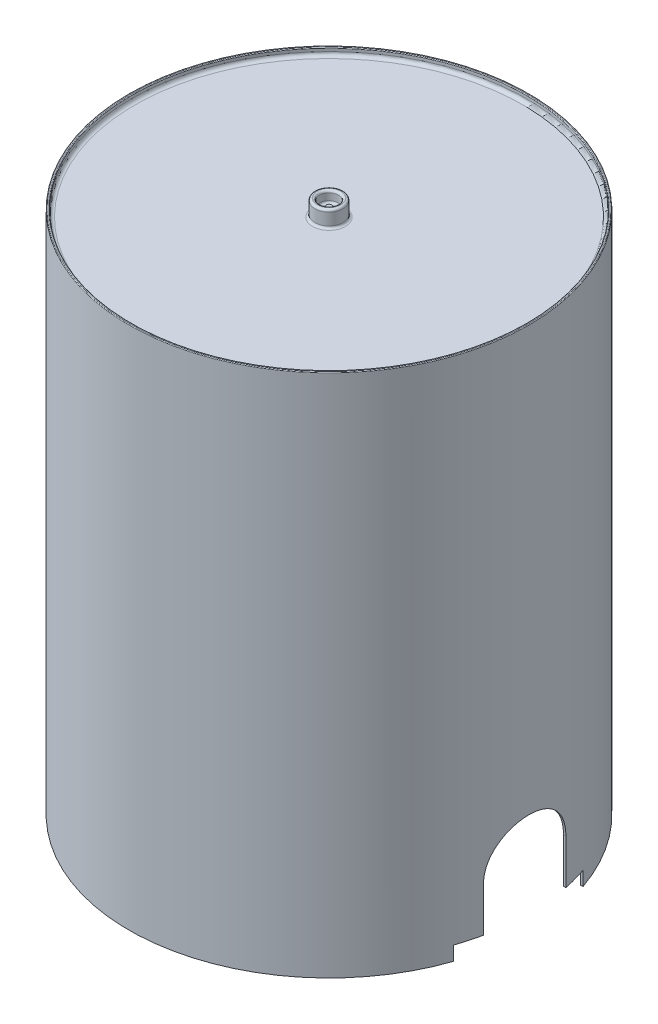
SolidWorks part; units mm, degrees
ref_plane "Plan de face" through (0, 0, 0) normal (0, 0, 1) x (1, 0, 0)
ref_plane "Plan de dessus" through (0, 0, 0) normal (0, 1, 0) x (1, 0, 0)
ref_plane "Plan de droite" through (0, 0, 0) normal (1, 0, 0) x (0, 0, -1)
sketch "Esquisse2" plane through (0, 0, 0) normal (0, 0, 1) x (1, 0, 0)
  line L0 (0, 220) -> (0, 219)
  line L1 (0, 0) -> (85, 0) construction
  line L2 (0, 0) -> (0, 220) construction
  line L3 (0, 220) -> (85, 220) construction
  line L4 (85, 0) -> (85, 220)
  line L5 (0, 219) -> (79, 219)
  line L6 (84, 214) -> (84, 0)
  line L7 (84, 0) -> (85, 0)
  line L8 (0, 220) -> (0, 224)
  line L9 (0, 224) -> (1, 224)
  line L10 (1, 224) -> (1, 223.1941)
  line L11 (1.95, 222.2441) -> (3.05, 222.2441)
  line L12 (4, 223.1941) -> (4, 226.05)
  line L13 (4.95, 227) -> (5.05, 227)
  line L14 (6, 226.05) -> (6, 220.95)
  line L15 (85, 220) -> (85, 222.7)
  line L16 (84.7, 223) -> (84.3, 223)
  line L17 (84, 222.7) -> (84, 221.5)
  line L18 (82.5, 220) -> (6.95, 220)
  arc A0 (84, 221.5) -> (82.5, 220) centre (82.5, 221.5) cw
  arc A1 (85, 222.7) -> (84.7, 223) centre (84.7, 222.7) ccw
  arc A2 (5.05, 227) -> (6, 226.05) centre (5.05, 226.05) cw
  arc A3 (4, 226.05) -> (4.95, 227) centre (4.95, 226.05) cw
  arc A4 (6, 220.95) -> (6.95, 220) centre (6.95, 220.95) ccw
  arc A5 (3.05, 222.2441) -> (4, 223.1941) centre (3.05, 223.1941) ccw
  arc A6 (1, 223.1941) -> (1.95, 222.2441) centre (1.95, 223.1941) ccw
  arc A7 (84.3, 223) -> (84, 222.7) centre (84.3, 222.7) ccw
  arc A8 (84, 214) -> (79, 219) centre (79, 214) ccw
  point P22 (6, 227)
  point P25 (4, 227)
  point P28 (6, 220)
  point P31 (4, 222.2441)
  point P34 (1, 222.2441)
  point P35 (84, 220)
  point P38 (85, 223)
  point P41 (84, 223)
  dimension "D5" = 1
  dimension "D11" = 0.95
  dimension "D13" = 1.5
  dimension "D14" = 0.3
  dimension "D15" = 5
  dimension "D1" = 85
  dimension "D2" = 220
  dimension "D3" = 1
  dimension "D4" = 1
  dimension "D6" = 4
  dimension "D7" = 7
  dimension "D8" = 1
  dimension "D9" = 3
  dimension "D10" = 2
  dimension "D12" = 3
revolve "Révolution1" add sketch "Esquisse2" angle 360 about L2
sketch "Esquisse3" plane through (0, 0, 0) normal (1, 0, 0) x (0, 0, -1)
  line L0 (0, 0) -> (0, 222.7) construction
  line L1 (-85, 222.7) -> (85, 222.7) construction
  line L2 (-85, 0) -> (85, 0) construction
  line L3 (-17.5, 25) -> (-17.5, 6)
  line L4 (-17.5, 6) -> (-27.5, 6)
  line L5 (-27.5, 6) -> (-27.5, 0)
  line L6 (-27.5, 0) -> (27.5, 0)
  line L7 (27.5, 0) -> (27.5, 6)
  line L8 (27.5, 6) -> (17.5, 6)
  line L9 (17.5, 6) -> (17.5, 25)
  circle A0 centre (0, 25) radius 17.5 construction
  arc A1 (-17.5, 25) -> (17.5, 25) centre (0, 25) cw
  dimension "D1" = 25
  dimension "D5" = 6
  dimension "D2" = 55
  dimension "D3" = 27.5
  dimension "D4" = 10
extrude "Enlèv. mat.-Extru.2" cut sketch "Esquisse3" against normal through all and the other way through all
